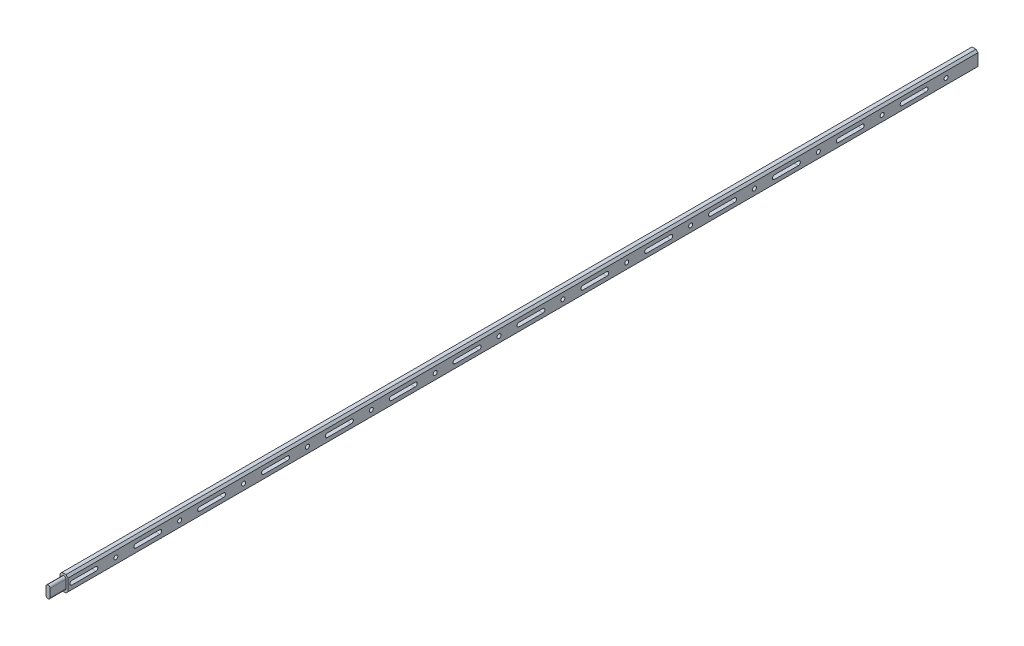
SolidWorks part; units mm, degrees
material "6061-T6 (SS)"
ref_plane "Front Plane" through (0, 0, 0) normal (0, 0, 1) x (1, 0, 0)
ref_plane "Top Plane" through (0, 0, 0) normal (0, 1, 0) x (1, 0, 0)
ref_plane "Right Plane" through (0, 0, 0) normal (1, 0, 0) x (0, 0, -1)
sketch "Sketch1" plane through (0, 0, 0) normal (0, 0, 1) x (1, 0, 0)
  line L0 (0, 11.1125) -> (1.5875, 12.7)
  line L1 (1.5875, 0) -> (4.7625, 0)
  line L2 (0, 1.5875) -> (0, 11.1125)
  line L3 (1.5875, 12.7) -> (4.7625, 12.7)
  line L4 (6.35, 1.5875) -> (6.35, 11.1125)
  line L5 (4.7625, 12.7) -> (6.35, 11.1125)
  line L6 (4.7625, 0) -> (6.35, 1.5875)
  line L7 (0, 1.5875) -> (1.5875, 0)
  point P0 (0, 0)
  point P1 (6.35, 12.7)
  point P2 (0, 12.7)
  point P3 (6.35, 0)
  dimension "D1" = 6.35
  dimension "D2" = 12.7
extrude "Boss-Extrude1" add sketch "Sketch1" along normal blind 749.3
sketch "Sketch2" plane through (0, 0, 749.3) normal (0, 0, 1) x (1, 0, 0)
  line L0 (6.35, 6.35) -> (0, 6.35) construction
  line L1 (6.35, 1.5875) -> (6.35, 11.1125) construction
  line L2 (0, 11.1125) -> (0, 1.5875) construction
  line L3 (3.175, 9.525) -> (3.175, 3.175) construction
  line L4 (1.5875, 0) -> (4.7625, 0) construction
  line L5 (3.175, 0) -> (3.175, 12.7) construction
  line L6 (4.7625, 12.7) -> (1.5875, 12.7) construction
  line L7 (4.7625, 9.525) -> (4.7625, 3.175)
  line L8 (1.5875, 9.525) -> (1.5875, 3.175)
  arc A0 (4.7625, 9.525) -> (1.5875, 9.525) centre (3.175, 9.525) ccw
  arc A1 (1.5875, 3.175) -> (4.7625, 3.175) centre (3.175, 3.175) ccw
  point P14 (3.175, 6.35)
extrude "Boss-Extrude2" add sketch "Sketch2" along normal blind 12.7
sketch "Sketch3" plane through (0, 0, 0) normal (-1, 0, 0) x (0, 0, 1)
  line L0 (749.3, 12.7) -> (0, 12.7) construction
  line L1 (0, 0) -> (25.4, 0)
  line L2 (0, 0) -> (0, 12.7)
  line L3 (0, 12.7) -> (25.4, 12.7)
  line L4 (25.4, 0) -> (25.4, 12.7)
  dimension "D1" = 25.4
extrude "Cut-Extrude1" cut sketch "Sketch3" against normal blind 6.35
sketch "Sketch4" plane through (0, 0, 0) normal (-1, 0, 0) x (0, 0, 1)
  line L0 (66.675, 6.35) -> (85.725, 6.35) construction
  line L1 (25.4, 1.5875) -> (25.4, 11.1125) construction
  line L2 (66.675, 7.9375) -> (85.725, 7.9375)
  line L3 (66.675, 4.7625) -> (85.725, 4.7625)
  line L5 (117.475, 6.35) -> (136.525, 6.35) construction
  line L6 (117.475, 7.9375) -> (136.525, 7.9375)
  line L7 (117.475, 4.7625) -> (136.525, 4.7625)
  line L8 (168.275, 6.35) -> (187.325, 6.35) construction
  line L9 (168.275, 7.9375) -> (187.325, 7.9375)
  line L10 (168.275, 4.7625) -> (187.325, 4.7625)
  line L11 (219.075, 6.35) -> (238.125, 6.35) construction
  line L12 (219.075, 7.9375) -> (238.125, 7.9375)
  line L13 (219.075, 4.7625) -> (238.125, 4.7625)
  line L14 (269.875, 6.35) -> (288.925, 6.35) construction
  line L15 (269.875, 7.9375) -> (288.925, 7.9375)
  line L16 (269.875, 4.7625) -> (288.925, 4.7625)
  line L17 (320.675, 6.35) -> (339.725, 6.35) construction
  line L18 (320.675, 7.9375) -> (339.725, 7.9375)
  line L19 (320.675, 4.7625) -> (339.725, 4.7625)
  line L20 (371.475, 6.35) -> (390.525, 6.35) construction
  line L21 (371.475, 7.9375) -> (390.525, 7.9375)
  line L22 (371.475, 4.7625) -> (390.525, 4.7625)
  line L23 (422.275, 6.35) -> (441.325, 6.35) construction
  line L24 (422.275, 7.9375) -> (441.325, 7.9375)
  line L25 (422.275, 4.7625) -> (441.325, 4.7625)
  line L26 (473.075, 6.35) -> (492.125, 6.35) construction
  line L27 (473.075, 7.9375) -> (492.125, 7.9375)
  line L28 (473.075, 4.7625) -> (492.125, 4.7625)
  line L29 (523.875, 6.35) -> (542.925, 6.35) construction
  line L30 (523.875, 7.9375) -> (542.925, 7.9375)
  line L31 (523.875, 4.7625) -> (542.925, 4.7625)
  line L32 (574.675, 6.35) -> (593.725, 6.35) construction
  line L33 (574.675, 7.9375) -> (593.725, 7.9375)
  line L34 (574.675, 4.7625) -> (593.725, 4.7625)
  line L35 (625.475, 6.35) -> (644.525, 6.35) construction
  line L36 (625.475, 7.9375) -> (644.525, 7.9375)
  line L37 (625.475, 4.7625) -> (644.525, 4.7625)
  line L38 (676.275, 6.35) -> (695.325, 6.35) construction
  line L39 (676.275, 7.9375) -> (695.325, 7.9375)
  line L40 (676.275, 4.7625) -> (695.325, 4.7625)
  line L41 (727.075, 6.35) -> (746.125, 6.35) construction
  line L42 (727.075, 7.9375) -> (746.125, 7.9375)
  line L43 (727.075, 4.7625) -> (746.125, 4.7625)
  line L44 (101.6, 11.1125) -> (101.6, 1.5875)
  line L45 (749.3, 11.1125) -> (25.4, 11.1125) construction
  line L46 (749.3, 1.5875) -> (25.4, 1.5875) construction
  arc A0 (66.675, 7.9375) -> (66.675, 4.7625) centre (66.675, 6.35) ccw
  arc A1 (85.725, 4.7625) -> (85.725, 7.9375) centre (85.725, 6.35) ccw
  arc A2 (117.475, 7.9375) -> (117.475, 4.7625) centre (117.475, 6.35) ccw
  arc A3 (136.525, 4.7625) -> (136.525, 7.9375) centre (136.525, 6.35) ccw
  arc A4 (168.275, 7.9375) -> (168.275, 4.7625) centre (168.275, 6.35) ccw
  arc A5 (187.325, 4.7625) -> (187.325, 7.9375) centre (187.325, 6.35) ccw
  arc A6 (219.075, 7.9375) -> (219.075, 4.7625) centre (219.075, 6.35) ccw
  arc A7 (238.125, 4.7625) -> (238.125, 7.9375) centre (238.125, 6.35) ccw
  arc A8 (269.875, 7.9375) -> (269.875, 4.7625) centre (269.875, 6.35) ccw
  arc A9 (288.925, 4.7625) -> (288.925, 7.9375) centre (288.925, 6.35) ccw
  arc A10 (320.675, 7.9375) -> (320.675, 4.7625) centre (320.675, 6.35) ccw
  arc A11 (339.725, 4.7625) -> (339.725, 7.9375) centre (339.725, 6.35) ccw
  arc A12 (371.475, 7.9375) -> (371.475, 4.7625) centre (371.475, 6.35) ccw
  arc A13 (390.525, 4.7625) -> (390.525, 7.9375) centre (390.525, 6.35) ccw
  arc A14 (422.275, 7.9375) -> (422.275, 4.7625) centre (422.275, 6.35) ccw
  arc A15 (441.325, 4.7625) -> (441.325, 7.9375) centre (441.325, 6.35) ccw
  arc A16 (473.075, 7.9375) -> (473.075, 4.7625) centre (473.075, 6.35) ccw
  arc A17 (492.125, 4.7625) -> (492.125, 7.9375) centre (492.125, 6.35) ccw
  arc A18 (523.875, 7.9375) -> (523.875, 4.7625) centre (523.875, 6.35) ccw
  arc A19 (542.925, 4.7625) -> (542.925, 7.9375) centre (542.925, 6.35) ccw
  arc A20 (574.675, 7.9375) -> (574.675, 4.7625) centre (574.675, 6.35) ccw
  arc A21 (593.725, 4.7625) -> (593.725, 7.9375) centre (593.725, 6.35) ccw
  arc A22 (625.475, 7.9375) -> (625.475, 4.7625) centre (625.475, 6.35) ccw
  arc A23 (644.525, 4.7625) -> (644.525, 7.9375) centre (644.525, 6.35) ccw
  arc A24 (676.275, 7.9375) -> (676.275, 4.7625) centre (676.275, 6.35) ccw
  arc A25 (695.325, 4.7625) -> (695.325, 7.9375) centre (695.325, 6.35) ccw
  arc A26 (727.075, 7.9375) -> (727.075, 4.7625) centre (727.075, 6.35) ccw
  arc A27 (746.125, 4.7625) -> (746.125, 7.9375) centre (746.125, 6.35) ccw
  circle A28 centre (101.6, 6.35) radius 1.5875
  circle A29 centre (152.4, 6.35) radius 1.5875
  circle A30 centre (203.2, 6.35) radius 1.5875
  circle A31 centre (254, 6.35) radius 1.5875
  circle A32 centre (304.8, 6.35) radius 1.5875
  circle A33 centre (355.6, 6.35) radius 1.5875
  circle A34 centre (406.4, 6.35) radius 1.5875
  circle A35 centre (457.2, 6.35) radius 1.5875
  circle A36 centre (508, 6.35) radius 1.5875
  circle A37 centre (558.8, 6.35) radius 1.5875
  circle A38 centre (609.6, 6.35) radius 1.5875
  circle A39 centre (660.4, 6.35) radius 1.5875
  circle A40 centre (711.2, 6.35) radius 1.5875
  point P6 (76.2, 6.35)
  point P15 (127, 6.35)
  point P22 (177.8, 6.35)
  point P29 (228.6, 6.35)
  point P36 (279.4, 6.35)
  point P43 (330.2, 6.35)
  point P50 (381, 6.35)
  point P57 (431.8, 6.35)
  point P64 (482.6, 6.35)
  point P71 (533.4, 6.35)
  point P78 (584.2, 6.35)
  point P85 (635, 6.35)
  point P92 (685.8, 6.35)
  point P99 (736.6, 6.35)
  dimension "D2" = 14
  dimension "D4" = 3.175
  dimension "D1" = 50.8
  dimension "D3" = 76.2
  dimension "D5" = 13
extrude "Cut-Extrude2" cut sketch "Sketch4" against normal blind 70.358 contours L7 A3 L6 A2 | A29 | L3 A1 L2 A0 | A28 | L10 A5 L9 A4 | A30 | L13 A7 L12 A6 | A31 | L16 A9 L15 A8 | A32 | L19 A11 L18 A10 | A33 | L22 A13 L21 A12 | A34 | L25 A15 L24 A14 | A35 | L28 A17 L27 A16 | A36 | L31 A19 L30 A18 | A37 | L34 A21 L33 A20 | A38 | L37 A23 L36 A22 | A39 | L40 A25 L39 A24 | A40 | L43 A27 L42 A26
sketch "Sketch5" plane through (0, 0, 0) normal (-1, 0, 0) x (0, 0, 1)
  line L0 (25.4, 1.5875) -> (25.4, 11.1125) construction
  line L1 (749.3, 12.7) -> (25.4, 12.7) construction
  circle A0 centre (50.8, 6.35) radius 1.5875
  dimension "D1" = 3.175
  dimension "D2" = 25.4
  dimension "D3" = 6.35
extrude "Cut-Extrude3" cut sketch "Sketch5" against normal blind 70.358
